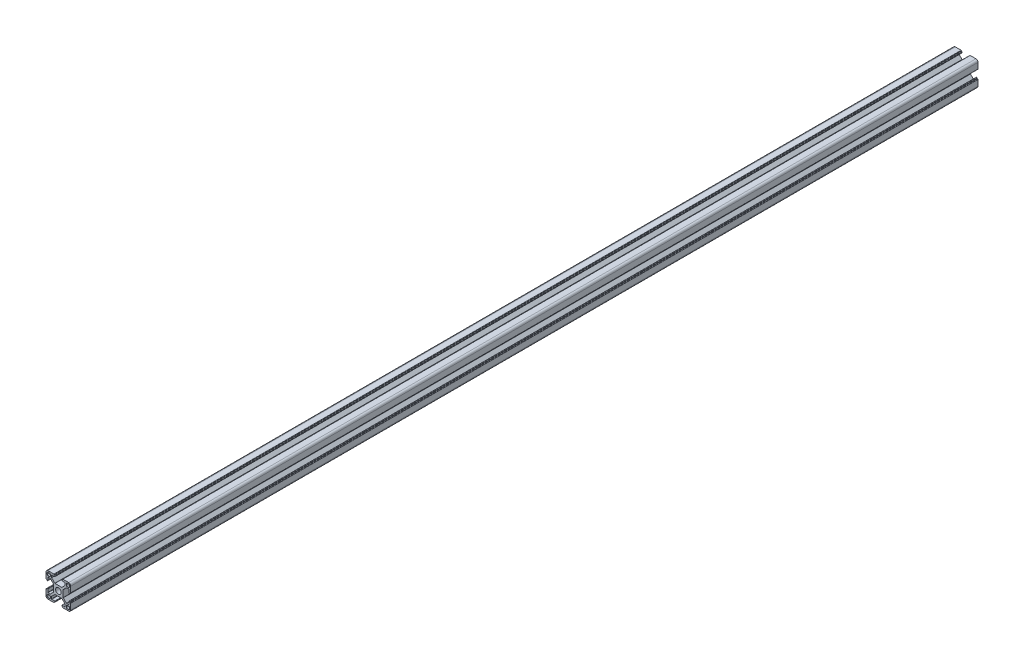
SolidWorks part; units mm, degrees
ref_plane "Front Plane" through (0, 0, 0) normal (0, 0, 1) x (1, 0, 0)
ref_plane "Top Plane" through (0, 0, 0) normal (0, 1, 0) x (1, 0, 0)
ref_plane "Right Plane" through (0, 0, 0) normal (1, 0, 0) x (0, 0, -1)
sketch "Model" plane through (0, 0, 0) normal (0, 0, 1) x (1, 0, 0)
  line L0 (21.5, 27) -> (25, 27)
  line L1 (27, 25) -> (27, 21.5)
  line L2 (25, 19.5) -> (21.5, 19.5)
  line L3 (19.5, 21.5) -> (19.5, 25)
  line L4 (21.5, -27) -> (25, -27)
  line L5 (27, -25) -> (27, -21.5)
  line L6 (25, -19.5) -> (21.5, -19.5)
  line L7 (19.5, -21.5) -> (19.5, -25)
  line L8 (0, 11.6) -> (-8.2402, 11.6)
  line L9 (-8.6645, 11.7757) -> (-16.3243, 19.4355)
  line L10 (-16.5, 19.8598) -> (-16.5, 25)
  line L11 (-15.9, 25.6) -> (-8.8, 25.6)
  line L12 (-8.2, 26.2) -> (-8.2, 27.4)
  line L13 (-8.8, 28) -> (-9.8, 28)
  line L14 (-10.4, 28.6) -> (-10.4, 29.4)
  line L15 (-11, 30) -> (-25, 30)
  line L16 (-30, 25) -> (-30, 11)
  line L17 (-29.4, 10.4) -> (-28.6, 10.4)
  line L18 (-28, 9.8) -> (-28, 8.8)
  line L19 (-27.4, 8.2) -> (-26.2, 8.2)
  line L20 (-25.6, 8.8) -> (-25.6, 15.9)
  line L21 (-25, 16.5) -> (-19.8598, 16.5)
  line L22 (-19.4355, 16.3243) -> (-11.7757, 8.6645)
  line L23 (-11.6, 8.2402) -> (-11.6, 0)
  line L24 (-11.6, 0) -> (-11.6, -8.2402)
  line L25 (-11.7757, -8.6645) -> (-19.4355, -16.3243)
  line L26 (-19.8598, -16.5) -> (-25, -16.5)
  line L27 (-25.6, -15.9) -> (-25.6, -8.8)
  line L28 (-26.2, -8.2) -> (-27.4, -8.2)
  line L29 (-28, -8.8) -> (-28, -9.8)
  line L30 (-28.6, -10.4) -> (-29.4, -10.4)
  line L31 (-30, -11) -> (-30, -25)
  line L32 (-25, -30) -> (-11, -30)
  line L33 (-10.4, -29.4) -> (-10.4, -28.6)
  line L34 (-9.8, -28) -> (-8.8, -28)
  line L35 (-8.2, -27.4) -> (-8.2, -26.2)
  line L36 (-8.8, -25.6) -> (-15.9, -25.6)
  line L37 (-16.5, -25) -> (-16.5, -19.8598)
  line L38 (-16.3243, -19.4355) -> (-8.6645, -11.7757)
  line L39 (-8.2402, -11.6) -> (0, -11.6)
  line L40 (0, -11.6) -> (8.2402, -11.6)
  line L41 (8.6645, -11.7757) -> (16.3243, -19.4355)
  line L42 (16.5, -19.8598) -> (16.5, -25)
  line L43 (15.9, -25.6) -> (8.8, -25.6)
  line L44 (8.2, -26.2) -> (8.2, -27.4)
  line L45 (8.8, -28) -> (9.8, -28)
  line L46 (10.4, -28.6) -> (10.4, -29.4)
  line L47 (11, -30) -> (25, -30)
  line L48 (30, -25) -> (30, -11)
  line L49 (29.4, -10.4) -> (28.6, -10.4)
  line L50 (28, -9.8) -> (28, -8.8)
  line L51 (27.4, -8.2) -> (26.2, -8.2)
  line L52 (25.6, -8.8) -> (25.6, -15.9)
  line L53 (25, -16.5) -> (19.8598, -16.5)
  line L54 (19.4355, -16.3243) -> (11.7757, -8.6645)
  line L55 (11.6, -8.2402) -> (11.6, 0)
  line L56 (11.6, 0) -> (11.6, 8.2402)
  line L57 (11.7757, 8.6645) -> (19.6113, 16.5)
  line L58 (19.6113, 16.5) -> (25, 16.5)
  line L59 (25.6, 15.9) -> (25.6, 8.8)
  line L60 (26.2, 8.2) -> (27.4, 8.2)
  line L61 (28, 8.8) -> (28, 9.8)
  line L62 (28.6, 10.4) -> (29.4, 10.4)
  line L63 (30, 11) -> (30, 25)
  line L64 (25, 30) -> (11, 30)
  line L65 (10.4, 29.4) -> (10.4, 28.6)
  line L66 (9.8, 28) -> (8.8, 28)
  line L67 (8.2, 27.4) -> (8.2, 26.2)
  line L68 (8.8, 25.6) -> (15.9, 25.6)
  line L69 (16.5, 25) -> (16.5, 19.8598)
  line L70 (16.3243, 19.4355) -> (8.6645, 11.7757)
  line L71 (8.2402, 11.6) -> (0, 11.6)
  line L72 (-21.5, -27) -> (-25, -27)
  line L73 (-27, -25) -> (-27, -21.5)
  line L74 (-25, -19.5) -> (-21.5, -19.5)
  line L75 (-19.5, -21.5) -> (-19.5, -25)
  line L76 (-21.5, 27) -> (-25, 27)
  line L77 (-27, 25) -> (-27, 21.5)
  line L78 (-25, 19.5) -> (-21.5, 19.5)
  line L79 (-19.5, 21.5) -> (-19.5, 25)
  circle A0 centre (0, 0) radius 6.8
  arc A1 (21.5, 27) -> (19.5, 25) centre (21.5, 25) ccw
  arc A2 (27, 25) -> (25, 27) centre (25, 25) ccw
  arc A3 (25, 19.5) -> (27, 21.5) centre (25, 21.5) ccw
  arc A4 (19.5, 21.5) -> (21.5, 19.5) centre (21.5, 21.5) ccw
  arc A5 (19.5, -25) -> (21.5, -27) centre (21.5, -25) ccw
  arc A6 (25, -27) -> (27, -25) centre (25, -25) ccw
  arc A7 (27, -21.5) -> (25, -19.5) centre (25, -21.5) ccw
  arc A8 (21.5, -19.5) -> (19.5, -21.5) centre (21.5, -21.5) ccw
  arc A9 (-8.6645, 11.7757) -> (-8.2402, 11.6) centre (-8.2402, 12.2) ccw
  arc A10 (-16.5, 19.8598) -> (-16.3243, 19.4355) centre (-15.9, 19.8598) ccw
  arc A11 (-15.9, 25.6) -> (-16.5, 25) centre (-15.9, 25) ccw
  arc A12 (-8.8, 25.6) -> (-8.2, 26.2) centre (-8.8, 26.2) ccw
  arc A13 (-8.2, 27.4) -> (-8.8, 28) centre (-8.8, 27.4) ccw
  arc A14 (-10.4, 28.6) -> (-9.8, 28) centre (-9.8, 28.6) ccw
  arc A15 (-10.4, 29.4) -> (-11, 30) centre (-11, 29.4) ccw
  arc A16 (-25, 30) -> (-30, 25) centre (-25, 25) ccw
  arc A17 (-30, 11) -> (-29.4, 10.4) centre (-29.4, 11) ccw
  arc A18 (-28, 9.8) -> (-28.6, 10.4) centre (-28.6, 9.8) ccw
  arc A19 (-28, 8.8) -> (-27.4, 8.2) centre (-27.4, 8.8) ccw
  arc A20 (-26.2, 8.2) -> (-25.6, 8.8) centre (-26.2, 8.8) ccw
  arc A21 (-25, 16.5) -> (-25.6, 15.9) centre (-25, 15.9) ccw
  arc A22 (-19.4355, 16.3243) -> (-19.8598, 16.5) centre (-19.8598, 15.9) ccw
  arc A23 (-11.6, 8.2402) -> (-11.7757, 8.6645) centre (-12.2, 8.2402) ccw
  arc A24 (-11.7757, -8.6645) -> (-11.6, -8.2402) centre (-12.2, -8.2402) ccw
  arc A25 (-19.8598, -16.5) -> (-19.4355, -16.3243) centre (-19.8598, -15.9) ccw
  arc A26 (-25.6, -15.9) -> (-25, -16.5) centre (-25, -15.9) ccw
  arc A27 (-25.6, -8.8) -> (-26.2, -8.2) centre (-26.2, -8.8) ccw
  arc A28 (-27.4, -8.2) -> (-28, -8.8) centre (-27.4, -8.8) ccw
  arc A29 (-28.6, -10.4) -> (-28, -9.8) centre (-28.6, -9.8) ccw
  arc A30 (-29.4, -10.4) -> (-30, -11) centre (-29.4, -11) ccw
  arc A31 (-30, -25) -> (-25, -30) centre (-25, -25) ccw
  arc A32 (-11, -30) -> (-10.4, -29.4) centre (-11, -29.4) ccw
  arc A33 (-9.8, -28) -> (-10.4, -28.6) centre (-9.8, -28.6) ccw
  arc A34 (-8.8, -28) -> (-8.2, -27.4) centre (-8.8, -27.4) ccw
  arc A35 (-8.2, -26.2) -> (-8.8, -25.6) centre (-8.8, -26.2) ccw
  arc A36 (-16.5, -25) -> (-15.9, -25.6) centre (-15.9, -25) ccw
  arc A37 (-16.3243, -19.4355) -> (-16.5, -19.8598) centre (-15.9, -19.8598) ccw
  arc A38 (-8.2402, -11.6) -> (-8.6645, -11.7757) centre (-8.2402, -12.2) ccw
  arc A39 (8.6645, -11.7757) -> (8.2402, -11.6) centre (8.2402, -12.2) ccw
  arc A40 (16.5, -19.8598) -> (16.3243, -19.4355) centre (15.9, -19.8598) ccw
  arc A41 (15.9, -25.6) -> (16.5, -25) centre (15.9, -25) ccw
  arc A42 (8.8, -25.6) -> (8.2, -26.2) centre (8.8, -26.2) ccw
  arc A43 (8.2, -27.4) -> (8.8, -28) centre (8.8, -27.4) ccw
  arc A44 (10.4, -28.6) -> (9.8, -28) centre (9.8, -28.6) ccw
  arc A45 (10.4, -29.4) -> (11, -30) centre (11, -29.4) ccw
  arc A46 (25, -30) -> (30, -25) centre (25, -25) ccw
  arc A47 (30, -11) -> (29.4, -10.4) centre (29.4, -11) ccw
  arc A48 (28, -9.8) -> (28.6, -10.4) centre (28.6, -9.8) ccw
  arc A49 (28, -8.8) -> (27.4, -8.2) centre (27.4, -8.8) ccw
  arc A50 (26.2, -8.2) -> (25.6, -8.8) centre (26.2, -8.8) ccw
  arc A51 (25, -16.5) -> (25.6, -15.9) centre (25, -15.9) ccw
  arc A52 (19.4355, -16.3243) -> (19.8598, -16.5) centre (19.8598, -15.9) ccw
  arc A53 (11.6, -8.2402) -> (11.7757, -8.6645) centre (12.2, -8.2402) ccw
  arc A54 (11.7757, 8.6645) -> (11.6, 8.2402) centre (12.2, 8.2402) ccw
  arc A55 (25.6, 15.9) -> (25, 16.5) centre (25, 15.9) ccw
  arc A56 (25.6, 8.8) -> (26.2, 8.2) centre (26.2, 8.8) ccw
  arc A57 (27.4, 8.2) -> (28, 8.8) centre (27.4, 8.8) ccw
  arc A58 (28.6, 10.4) -> (28, 9.8) centre (28.6, 9.8) ccw
  arc A59 (29.4, 10.4) -> (30, 11) centre (29.4, 11) ccw
  arc A60 (30, 25) -> (25, 30) centre (25, 25) ccw
  arc A61 (11, 30) -> (10.4, 29.4) centre (11, 29.4) ccw
  arc A62 (9.8, 28) -> (10.4, 28.6) centre (9.8, 28.6) ccw
  arc A63 (8.8, 28) -> (8.2, 27.4) centre (8.8, 27.4) ccw
  arc A64 (8.2, 26.2) -> (8.8, 25.6) centre (8.8, 26.2) ccw
  arc A65 (16.5, 25) -> (15.9, 25.6) centre (15.9, 25) ccw
  arc A66 (16.3243, 19.4355) -> (16.5, 19.8598) centre (15.9, 19.8598) ccw
  arc A67 (8.2402, 11.6) -> (8.6645, 11.7757) centre (8.2402, 12.2) ccw
  arc A68 (-21.5, -27) -> (-19.5, -25) centre (-21.5, -25) ccw
  arc A69 (-27, -25) -> (-25, -27) centre (-25, -25) ccw
  arc A70 (-25, -19.5) -> (-27, -21.5) centre (-25, -21.5) ccw
  arc A71 (-19.5, -21.5) -> (-21.5, -19.5) centre (-21.5, -21.5) ccw
  arc A72 (-19.5, 25) -> (-21.5, 27) centre (-21.5, 25) ccw
  arc A73 (-25, 27) -> (-27, 25) centre (-25, 25) ccw
  arc A74 (-27, 21.5) -> (-25, 19.5) centre (-25, 21.5) ccw
  arc A75 (-21.5, 19.5) -> (-19.5, 21.5) centre (-21.5, 21.5) ccw
extrude "Boss-Extrude1" add sketch "Model" along normal blind 2200
scale "Scale1" bodies to scale 101 scale about centroid uniform scaling yes scale factor 0.5
